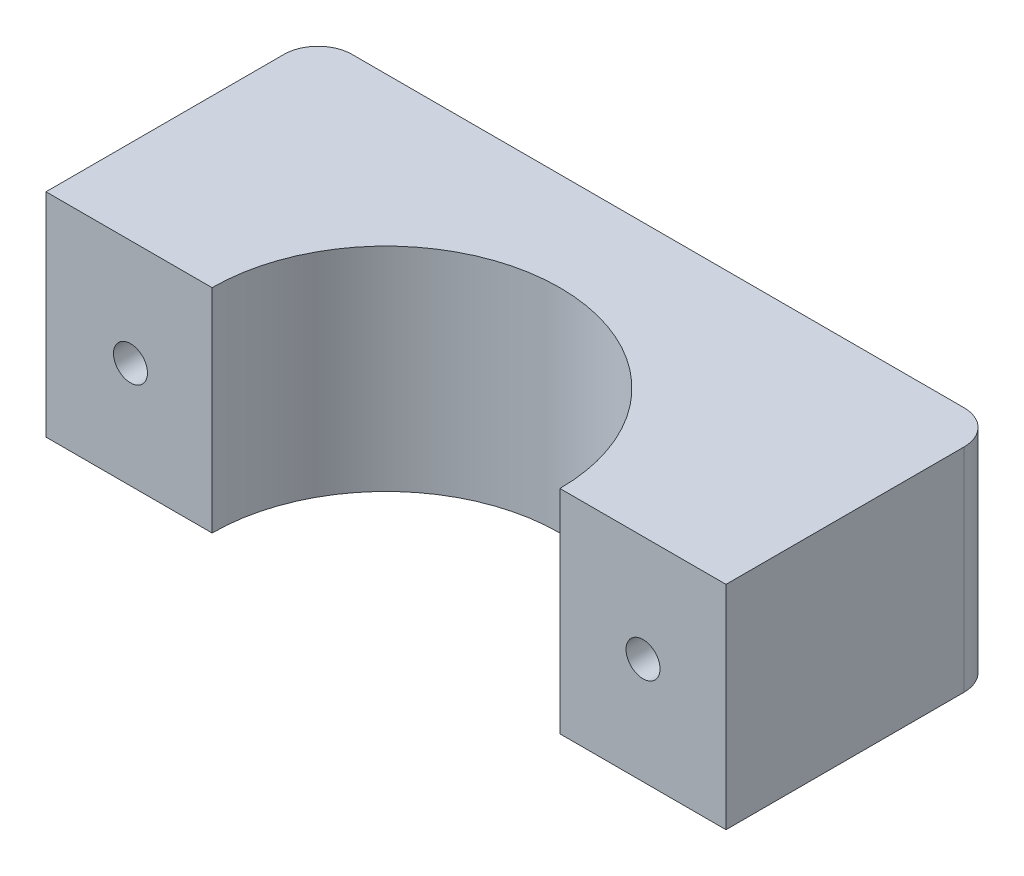
SolidWorks part; units mm, degrees
ref_plane "Front Plane" through (0, 0, 0) normal (0, 0, 1) x (1, 0, 0)
ref_plane "Top Plane" through (0, 0, 0) normal (0, 1, 0) x (1, 0, 0)
ref_plane "Right Plane" through (0, 0, 0) normal (1, 0, 0) x (0, 0, -1)
sketch "Sketch1" plane through (0, 0, 0) normal (0, 1, 0) x (1, 0, 0)
  line L1 (2.54, 0) -> (48.26, 0)
  line L2 (0, -2.54) -> (0, -20.32)
  line L3 (0, -20.32) -> (50.8, -20.32)
  line L4 (50.8, -2.54) -> (50.8, -20.32)
  circle A0 centre (25.4, -20.32) radius 12.9921
  arc A1 (48.26, 0) -> (50.8, -2.54) centre (48.26, -2.54) cw
  arc A2 (2.54, 0) -> (0, -2.54) centre (2.54, -2.54) ccw
  point P9 (50.8, 0)
  point P12 (0, 0)
  dimension "D1" = 25.9842
  dimension "D4" = 2.54
  dimension "D2" = 20.32
  dimension "D3" = 50.8
extrude "Boss-Extrude1" add sketch "Sketch1" along normal blind 15.875 contours L1 A2 L2 L3 A0 L4 A1
sketch "Sketch2" plane through (0, 0, 20.32) normal (0, 0, 1) x (1, 0, 0)
  line L0 (38.3921, 15.875) -> (38.3921, 0) construction
  line L1 (38.3921, 15.875) -> (50.8, 15.875) construction
  line L2 (0, 0) -> (12.4079, 0) construction
  line L3 (12.4079, 15.875) -> (12.4079, 0) construction
  circle A0 centre (6.3119, 7.9375) radius 1.27
  circle A1 centre (44.6024, 7.9375) radius 1.27
  dimension "D3" = 2.54
  dimension "D1" = 6.2103
  dimension "D2" = 7.9375
  dimension "D4" = 7.9375
  dimension "D5" = 6.096
extrude "Cut-Extrude1" cut sketch "Sketch2" against normal through all
sketch "Sketch3" plane through (0, 0, 0) normal (0, 0, -1) x (-1, 0, 0)
  circle A0 centre (-44.6024, 7.9375) radius 3.81
  circle A1 centre (-6.3119, 7.9375) radius 3.81
  dimension "D1" = 7.62
extrude "Cut-Extrude2" cut sketch "Sketch3" against normal blind 4.1275
